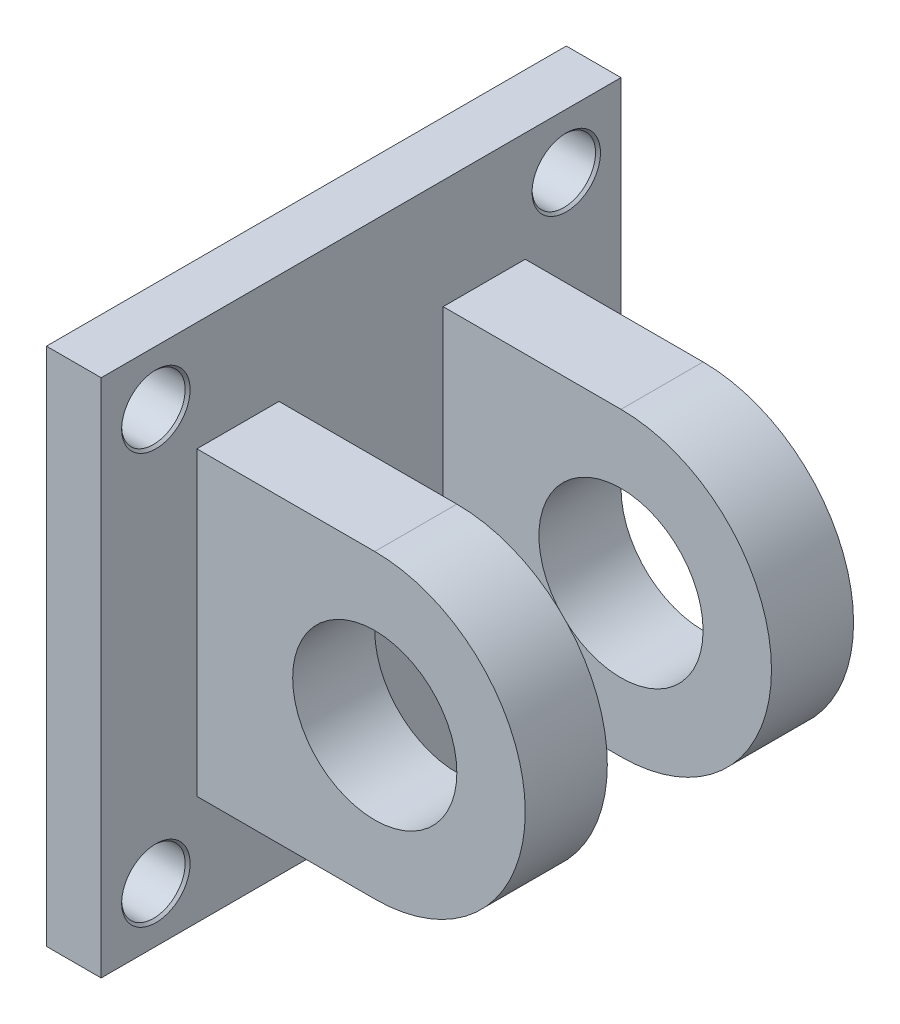
SolidWorks part; units mm, degrees
material "Cast Carbon Steel"
ref_plane "Front Plane" through (0, 0, 0) normal (0, 0, 1) x (1, 0, 0)
ref_plane "Top Plane" through (0, 0, 0) normal (0, 1, 0) x (1, 0, 0)
ref_plane "Right Plane" through (0, 0, 0) normal (1, 0, 0) x (0, 0, -1)
ref_plane "Plane4" through (25.4, 0, 0) normal (1, 0, 0) x (0, 0, -1)
sketch "Sketch1" plane through (25.4, 0, 0) normal (1, 0, 0) x (0, 0, -1)
  line L0 (-120.65, 120.65) -> (-120.65, -120.65)
  line L1 (-120.65, -120.65) -> (120.65, -120.65)
  line L2 (120.65, -120.65) -> (120.65, 120.65)
  line L3 (120.65, 120.65) -> (-120.65, 120.65)
extrude "Boss-Extrude1" add sketch "Sketch1" against normal blind 25.4
ref_plane "Plane5" through (0, 0, -76.2) normal (0, 0, -1) x (-1, 0, 0)
sketch "Sketch2" plane through (0, 0, -76.2) normal (0, 0, -1) x (-1, 0, 0)
  line L0 (-25.4, -69.85) -> (-25.4, 69.85)
  line L1 (-25.4, 69.85) -> (-107.95, 69.85)
  line L2 (-107.95, -69.85) -> (-25.4, -69.85)
  arc A0 (-107.95, 69.85) -> (-107.95, -69.85) centre (-107.95, 0) ccw
extrude "Boss-Extrude2" add sketch "Sketch2" against normal blind 38.1
ref_plane "Plane6" through (0, 0, 76.2) normal (0, 0, 1) x (1, 0, 0)
sketch "Sketch3" plane through (0, 0, 76.2) normal (0, 0, 1) x (1, 0, 0)
  line L0 (25.4, 69.85) -> (25.4, -69.85)
  line L1 (25.4, -69.85) -> (107.95, -69.85)
  line L2 (107.95, 69.85) -> (25.4, 69.85)
  arc A0 (107.95, -69.85) -> (107.95, 69.85) centre (107.95, 0) ccw
extrude "Boss-Extrude3" add sketch "Sketch3" against normal blind 38.1
hole_wizard "1-1/8 Clearance Hole1" positions "Sketch5" profile "Sketch4" hole size "1-1/8" standard "ANSI Inch"
sketch "Sketch5" plane through (0, 0, 0) normal (-1, 0, 0) x (0, 0, 1)
  point P0 (-95.25, -95.25)
  point P1 (95.25, -95.25)
sketch "Sketch4" plane through (0, -95.25, -95.25) normal (0, 1, 0) x (0, 0, 1)
  line L0 (0, 0) -> (0, 177.8)
  line L1 (0, 177.8) -> (14.7295, 177.8)
  line L2 (14.7295, 177.8) -> (14.7295, 0)
  line L5 (14.7295, 0) -> (0, 0)
  line L11 (0, -6.35) -> (0, 107.95) construction
  dimension "Thru Hole Dia." = 29.4589
  dimension "Thru Hole Depth" = 177.8
hole_wizard "1-1/8 Clearance Hole2" positions "Sketch7" profile "Sketch6" hole size "1-1/8" standard "ANSI Inch"
sketch "Sketch7" plane through (25.4, 0, 0) normal (1, 0, 0) x (0, 0, -1)
  point P0 (-95.25, 95.25)
  point P1 (95.25, 95.25)
sketch "Sketch6" plane through (25.4, 95.25, 95.25) normal (0, 1, 0) x (0, 0, -1)
  line L0 (0, 0) -> (0, 25.4)
  line L1 (0, 25.4) -> (14.7295, 25.4)
  line L2 (14.7295, 25.4) -> (14.7295, 0)
  line L5 (14.7295, 0) -> (0, 0)
  line L11 (0, -6.35) -> (0, 107.95) construction
  dimension "Thru Hole Dia." = 29.4589
  dimension "Thru Hole Depth" = 25.4
hole_wizard "Hole1" positions "Sketch9" profile "Sketch8" legacy
sketch "Sketch9" plane through (0, 0, 38.1) normal (0, 0, -1) x (-1, 0, 0)
  point P0 (-107.95, 0)
sketch "Sketch8" plane through (107.95, 0, 38.1) normal (1, 0, 0) x (0, 1, 0)
  line L0 (0, 0) -> (0, 82.55)
  line L1 (0, 82.55) -> (38.1, 82.55)
  line L2 (38.1, 82.55) -> (38.1, 0)
  line L3 (38.1, 0) -> (0, 0)
  line L4 (0, 110) -> (0, -10) construction
  dimension "Diameter" = 76.2
  dimension "Depth" = 82.55
hole_wizard "Hole2" positions "Sketch11" profile "Sketch10" legacy
sketch "Sketch11" plane through (0, 0, -38.1) normal (0, 0, 1) x (1, 0, 0)
  point P0 (107.95, 0)
sketch "Sketch10" plane through (107.95, 0, -38.1) normal (1, 0, 0) x (0, -1, 0)
  line L0 (0, 0) -> (0, 82.55)
  line L1 (0, 82.55) -> (38.1, 82.55)
  line L2 (38.1, 82.55) -> (38.1, 0)
  line L3 (38.1, 0) -> (0, 0)
  line L4 (0, 110) -> (0, -10) construction
  dimension "Diameter" = 76.2
  dimension "Depth" = 82.55
chamfer "Chamfer1" distance 1.1455 angle 45 8 edges at (25.4, -95.25, 80.5205) (25.4, -95.25, -109.9795) (0, -95.25, -80.5205) (0, 95.25, 80.5205) (0, -95.25, 109.9795) (0, 95.25, -109.9795) (25.4, 95.25, 80.5205) (25.4, 95.25, -109.9795)
